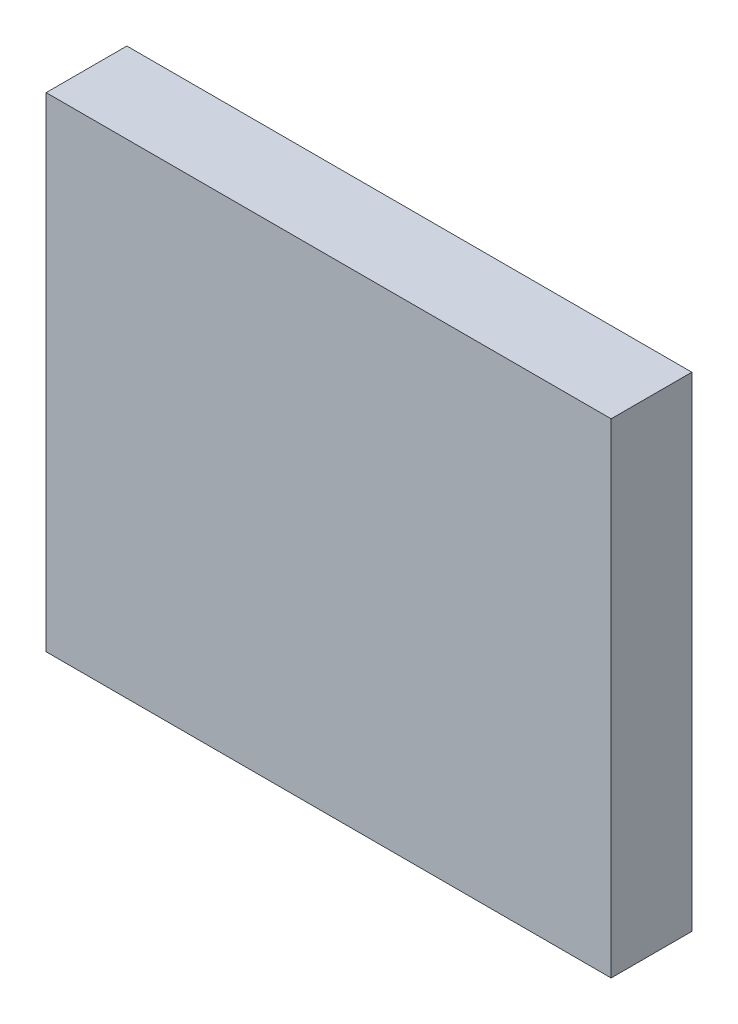
SolidWorks part; units mm, degrees
ref_plane "Alzado" through (0, 0, 0) normal (0, 0, 1) x (1, 0, 0)
ref_plane "Planta" through (0, 0, 0) normal (0, 1, 0) x (1, 0, 0)
ref_plane "Vista lateral" through (0, 0, 0) normal (1, 0, 0) x (0, 0, -1)
sketch "Croquis_base" plane through (0, 0, 0) normal (0, 1, 0) x (1, 0, 0)
  line L1 (-87.5, -12.5) -> (87.5, -12.5)
  line L2 (-87.5, -12.5) -> (-87.5, 12.5)
  line L3 (-87.5, 12.5) -> (87.5, 12.5)
  line L4 (87.5, -12.5) -> (87.5, 12.5)
  line L5 (-87.5, -12.5) -> (87.5, 12.5) construction
  line L6 (-87.5, 12.5) -> (87.5, -12.5) construction
  point P0 (0, 0)
  dimension "D1" = 87.5
  dimension "D2" = 12.5
extrude "Muro" add sketch "Croquis_base" along normal blind 150
sketch "Croquis_agujeros_montaje" plane through (0, 0, 0) normal (0, 1, 0) x (1, 0, 0)
  circle A0 centre (-50, 0) radius 4
  circle A1 centre (50, 0) radius 4
  dimension "D1" = 8
  dimension "D2" = 100
extrude "Agujero_inserto_M6" cut sketch "Croquis_agujeros_montaje" along normal blind 14
